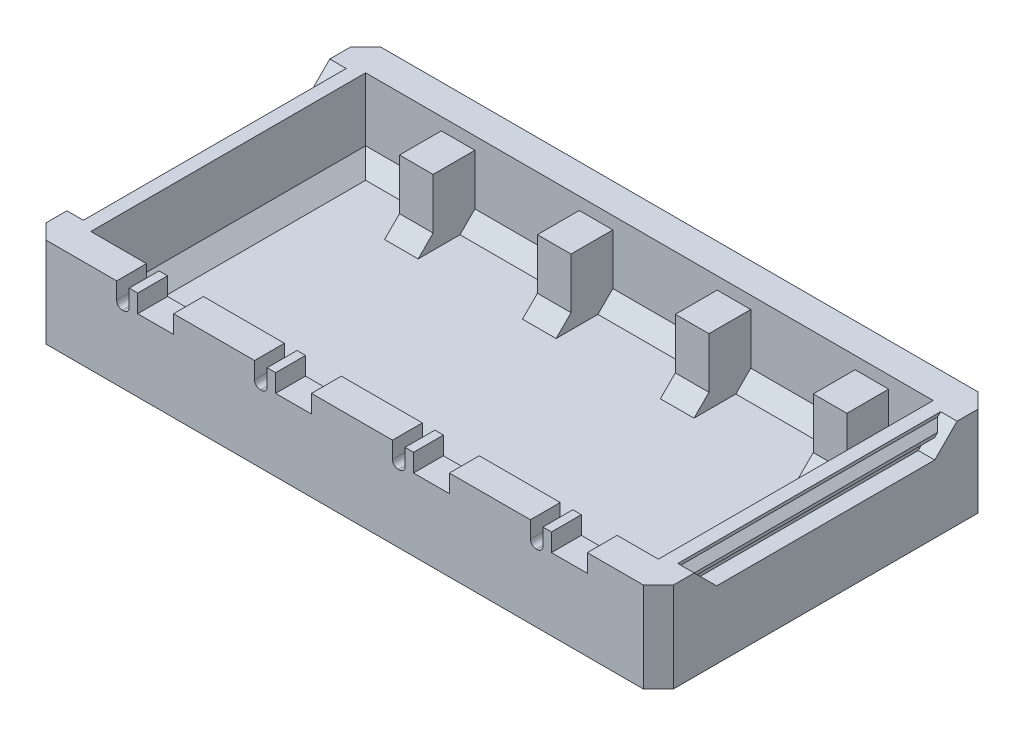
SolidWorks part; units mm, degrees
ref_plane "Front Plane" through (0, 0, 0) normal (0, 0, 1) x (1, 0, 0)
ref_plane "Top Plane" through (0, 0, 0) normal (0, 1, 0) x (1, 0, 0)
ref_plane "Right Plane" through (0, 0, 0) normal (1, 0, 0) x (0, 0, -1)
sketch "Sketch1" plane through (0, 0, 0) normal (0, 1, 0) x (1, 0, 0)
  line L0 (-98.0961, -62.3378) -> (-93.9186, -62.3378)
  line L1 (-36.993, -62.3378) -> (-32.8155, -62.3378)
  line L3 (-91.424, 17.3176) -> (-116.5294, 17.3176)
  line L4 (-120.5294, 26.5283) -> (130.2431, 26.5283)
  line L5 (130.2431, 26.5283) -> (144.4706, 12.3007)
  line L6 (144.4706, 12.3007) -> (144.4706, -73.4717)
  line L7 (-120.5294, -73.4717) -> (-120.5294, 26.5283)
  line L8 (-120.5294, -73.4717) -> (144.4706, -73.4717)
  line L9 (-13.46, -3.1584) -> (-13.46, 8.5813)
  line L10 (-13.46, 8.5813) -> (-19.078, 8.5283)
  line L11 (-19.078, 8.5283) -> (-19.078, 17.3176)
  line L12 (-19.078, 17.3176) -> (-30.321, 17.3176)
  line L13 (-30.321, 17.3176) -> (-30.321, 8.5283)
  line L14 (-30.321, 8.5283) -> (-49.7, 8.5283)
  line L15 (-49.7, 8.5283) -> (-49.7, -62.3378)
  line L16 (-49.7, -62.3378) -> (-36.993, -62.3378)
  line L17 (-36.993, -62.3378) -> (-36.993, -66.4407)
  line L18 (-36.993, -66.4407) -> (-35.5069, -66.4407)
  line L19 (-35.5069, -66.4407) -> (-35.5069, -73.7817)
  line L20 (-35.5069, -73.7817) -> (-34.1569, -73.7817)
  line L21 (-34.1569, -73.7817) -> (-34.1569, -66.2817)
  line L22 (-34.1569, -66.2817) -> (-32.8155, -66.2817)
  line L23 (-32.8155, -66.2817) -> (-32.8155, -61.9717)
  line L24 (-32.8155, -61.9717) -> (-29.96, -61.9717)
  line L25 (-29.96, -61.9717) -> (-29.96, -96.1308)
  line L26 (-29.96, -96.1308) -> (-17.96, -96.1308)
  line L27 (-17.96, -96.1308) -> (-17.96, -61.9717)
  line L28 (-17.96, -61.9717) -> (-13.46, -61.9717)
  line L29 (-13.46, -61.9717) -> (-13.46, -56.6683)
  line L30 (-13.46, -56.6683) -> (-13.46, -3.1584)
  line L31 (50.8938, -3.1584) -> (50.8938, 8.5813)
  line L32 (50.8938, 8.5813) -> (45.2757, 8.5283)
  line L33 (45.2757, 8.5283) -> (45.2757, 17.3176)
  line L34 (45.2757, 17.3176) -> (34.0298, 17.3176)
  line L35 (34.0298, 17.3176) -> (34.0298, 8.5283)
  line L36 (34.0298, 8.5283) -> (14.65, 8.5283)
  line L37 (14.65, 8.5283) -> (14.65, -62.3378)
  line L38 (14.65, -62.3378) -> (27.3577, -62.3378)
  line L39 (27.3577, -62.3378) -> (27.3577, -66.4407)
  line L40 (27.3577, -66.4407) -> (28.8438, -66.4407)
  line L41 (28.8438, -66.4407) -> (28.8438, -73.7817)
  line L42 (28.8438, -73.7817) -> (30.1938, -73.7817)
  line L43 (30.1938, -73.7817) -> (30.1938, -66.2817)
  line L44 (30.1938, -66.2817) -> (31.5352, -66.2817)
  line L45 (31.5352, -66.2817) -> (31.5352, -61.9717)
  line L46 (31.5352, -61.9717) -> (34.3938, -61.9717)
  line L47 (34.3938, -61.9717) -> (34.3938, -96.1308)
  line L48 (34.3938, -96.1308) -> (46.3938, -96.1308)
  line L49 (46.3938, -96.1308) -> (46.3938, -61.9717)
  line L50 (46.3938, -61.9717) -> (50.8938, -61.9717)
  line L51 (50.8938, -61.9717) -> (50.8938, -56.6683)
  line L52 (50.8938, -56.6683) -> (50.8938, -3.1584)
  line L53 (118.1875, -3.1584) -> (118.1875, 8.5813)
  line L54 (118.1875, 8.5813) -> (112.5695, 8.5283)
  line L55 (112.5695, 8.5283) -> (112.5695, 17.3176)
  line L56 (112.5695, 17.3176) -> (101.3235, 17.3176)
  line L57 (101.3235, 17.3176) -> (101.3235, 8.5283)
  line L58 (101.3235, 8.5283) -> (81.9438, 8.5283)
  line L59 (81.9438, 8.5283) -> (81.9438, -62.3378)
  line L60 (81.9438, -62.3378) -> (94.6515, -62.3378)
  line L61 (94.6515, -62.3378) -> (94.6515, -66.4407)
  line L62 (94.6515, -66.4407) -> (96.1375, -66.4407)
  line L63 (96.1375, -66.4407) -> (96.1375, -73.7817)
  line L64 (96.1375, -73.7817) -> (97.4875, -73.7817)
  line L65 (97.4875, -73.7817) -> (97.4875, -66.2817)
  line L66 (97.4875, -66.2817) -> (98.829, -66.2817)
  line L67 (98.829, -66.2817) -> (98.829, -61.9717)
  line L68 (98.829, -61.9717) -> (101.6875, -61.9717)
  line L69 (101.6875, -61.9717) -> (101.6875, -96.1308)
  line L70 (101.6875, -96.1308) -> (113.6875, -96.1308)
  line L71 (113.6875, -96.1308) -> (113.6875, -61.9717)
  line L72 (113.6875, -61.9717) -> (118.1875, -61.9717)
  line L73 (118.1875, -61.9717) -> (118.1875, -56.6683)
  line L74 (118.1875, -56.6683) -> (118.1875, -3.1584)
  line L77 (-80.178, 17.3176) -> (-91.424, 17.3176)
  line L79 (-116.5294, 22.5283) -> (-116.5294, -69.4717)
  line L80 (-116.5294, -69.4717) -> (140.4706, -69.4717)
  line L81 (128.5862, 22.5283) -> (140.4706, 10.6439)
  line L83 (140.4706, -69.4717) -> (140.4706, 10.6439)
  line L84 (-116.5294, 22.5283) -> (128.5862, 22.5283)
  line L86 (-110.8038, -62.3378) -> (-98.0961, -62.3378)
  line L87 (-98.0961, -62.3378) -> (-98.0961, -66.4407)
  line L88 (-98.0961, -66.4407) -> (-96.61, -66.4407)
  line L89 (-96.61, -66.4407) -> (-96.61, -73.7817)
  line L90 (-96.61, -73.7817) -> (-95.26, -73.7817)
  line L91 (-95.26, -73.7817) -> (-95.26, -66.2817)
  line L92 (-95.26, -66.2817) -> (-93.9186, -66.2817)
  line L93 (-93.9186, -66.2817) -> (-93.9186, -61.9717)
  line L94 (-93.9186, -61.9717) -> (-91.06, -61.9717)
  line L95 (-91.06, -61.9717) -> (-91.06, -96.1308)
  line L96 (-91.06, -96.1308) -> (-79.06, -96.1308)
  line L97 (-79.06, -96.1308) -> (-79.06, -61.9717)
  line L98 (-79.06, -61.9717) -> (-74.56, -61.9717)
  line L99 (-74.56, -61.9717) -> (-74.56, -56.6683)
  line L101 (-116.5294, 17.3176) -> (-116.5294, 8.5283)
  line L102 (-116.5294, 8.5283) -> (140.4706, 8.5283)
  line L103 (140.4706, 8.5283) -> (140.4706, 10.6439)
  line L104 (133.7969, 17.3176) -> (-91.424, 17.3176)
  line L105 (27.3577, -62.3378) -> (31.5352, -62.3378)
  line L106 (94.6515, -62.3378) -> (98.829, -62.3378)
  line L107 (-91.424, 17.3176) -> (-91.424, 22.5283)
  line L108 (-91.424, 22.5283) -> (-80.178, 22.5283)
  line L109 (-80.178, 22.5283) -> (-80.178, 17.3176)
  line L110 (-30.321, 17.3176) -> (-30.321, 22.5283)
  line L111 (-30.321, 22.5283) -> (-19.078, 22.5283)
  line L112 (-19.078, 22.5283) -> (-19.078, 17.3176)
  line L113 (34.0298, 17.3176) -> (34.0298, 22.5283)
  line L114 (34.0298, 22.5283) -> (45.2757, 22.5283)
  line L115 (45.2757, 22.5283) -> (45.2757, 17.3176)
  line L116 (101.3235, 17.3176) -> (101.3235, 22.5283)
  line L117 (101.3235, 22.5283) -> (112.5695, 22.5283)
  line L118 (112.5695, 22.5283) -> (112.5695, 17.3176)
sketch "Sketch2" plane through (0, 0, 0) normal (0, 1, 0) x (1, 0, 0)
  line L3 (-116.5294, 22.5283) -> (128.5862, 22.5283) construction
  line L4 (79.4706, 22.5283) -> (79.4706, -69.4717)
  line L5 (-116.5294, -69.4717) -> (140.4706, -69.4717) construction
  line L8 (-110.5294, 22.5283) -> (79.4706, 22.5283)
  line L10 (-110.5294, 22.5283) -> (-110.5294, -69.4717)
  line L12 (-110.5294, -69.4717) -> (79.4706, -69.4717)
  line L19 (89.4706, -79.4717) -> (-120.5294, -79.4717)
  line L20 (-120.5294, -79.4717) -> (-120.5294, 32.5283)
  line L21 (-120.5294, 32.5283) -> (89.4706, 32.5283)
  line L22 (89.4706, -79.4717) -> (89.4706, 32.5283)
  dimension "D1" = 10
extrude "Boss-Extrude1" add sketch "Sketch2" along normal blind 30.16
sketch "Sketch3" plane through (0, 0, 0) normal (0, -1, 0) x (1, 0, 0)
  line L1 (-120.5294, 79.4717) -> (89.4706, 79.4717)
  line L2 (-120.5294, 79.4717) -> (-120.5294, -32.5283)
  line L3 (-120.5294, -32.5283) -> (89.4706, -32.5283)
  line L4 (89.4706, 79.4717) -> (89.4706, -32.5283)
extrude "Boss-Extrude2" add sketch "Sketch3" against normal blind 4 separate body
sketch "Sketch4" plane through (0, 4, 0) normal (0, 1, 0) x (1, 0, 0)
  line L0 (-73.9394, 22.5283) -> (-73.9394, 8.5283)
  line L1 (-116.5294, 22.5283) -> (128.5862, 22.5283) construction
  line L2 (-116.5294, 8.5283) -> (140.4706, 8.5283) construction
  line L3 (-73.9394, 8.5283) -> (-85.1894, 8.5283)
  line L4 (-85.1894, 8.5283) -> (-85.1894, 22.5283)
  line L5 (-85.1894, 22.5283) -> (-73.9394, 22.5283)
  line L6 (-110.5294, 22.5283) -> (-110.5294, -69.4717) construction
  line L7 (-27.7694, 22.5283) -> (-27.7694, 8.5283)
  line L8 (-27.7694, 8.5283) -> (-39.0194, 8.5283)
  line L9 (-39.0194, 8.5283) -> (-39.0194, 22.5283)
  line L10 (-39.0194, 22.5283) -> (-27.7694, 22.5283)
  line L11 (18.4006, 22.5283) -> (18.4006, 8.5283)
  line L12 (18.4006, 8.5283) -> (7.1506, 8.5283)
  line L13 (7.1506, 8.5283) -> (7.1506, 22.5283)
  line L14 (7.1506, 22.5283) -> (18.4006, 22.5283)
  line L15 (64.5706, 22.5283) -> (64.5706, 8.5283)
  line L16 (64.5706, 8.5283) -> (53.3206, 8.5283)
  line L17 (53.3206, 8.5283) -> (53.3206, 22.5283)
  line L18 (53.3206, 22.5283) -> (64.5706, 22.5283)
  dimension "D1" = 36.59
  dimension "D2" = 11.25
  dimension "D3" = 11.25
  dimension "D4" = 46.17
  dimension "D5" = 11.25
  dimension "D6" = 46.17
  dimension "D7" = 11.25
  dimension "D8" = 46.17
extrude "Boss-Extrude3" add sketch "Sketch4" along normal blind 22
sketch "Sketch5" plane through (0, 30.16, 0) normal (0, 1, 0) x (1, 0, 0)
  line L0 (-84.8294, -69.4717) -> (-84.8294, -79.4717)
  line L1 (-116.5294, -69.4717) -> (140.4706, -69.4717) construction
  line L2 (-120.5294, -79.4717) -> (89.4706, -79.4717) construction
  line L3 (-85.1894, 22.5283) -> (-85.1894, 8.5283) construction
  line L4 (-72.8294, -69.4717) -> (-72.8294, -79.4717)
  line L5 (-84.8294, -69.4717) -> (-72.8294, -69.4717)
  line L6 (-72.8294, -79.4717) -> (-84.8294, -79.4717)
  line L7 (-38.6594, -69.4717) -> (-38.6594, -79.4717)
  line L8 (-26.6594, -69.4717) -> (-26.6594, -79.4717)
  line L9 (-38.6594, -69.4717) -> (-26.6594, -69.4717)
  line L10 (-26.6594, -79.4717) -> (-38.6594, -79.4717)
  line L11 (7.5106, -69.4717) -> (7.5106, -79.4717)
  line L12 (19.5106, -69.4717) -> (19.5106, -79.4717)
  line L13 (7.5106, -69.4717) -> (19.5106, -69.4717)
  line L14 (19.5106, -79.4717) -> (7.5106, -79.4717)
  line L15 (53.6806, -69.4717) -> (53.6806, -79.4717)
  line L16 (65.6806, -69.4717) -> (65.6806, -79.4717)
  line L17 (53.6806, -69.4717) -> (65.6806, -69.4717)
  line L18 (65.6806, -79.4717) -> (53.6806, -79.4717)
  dimension "D1" = 0.36
  dimension "D2" = 12
  dimension "D3" = 12
  dimension "D4" = 12
  dimension "D5" = 12
  dimension "D6" = 46.17
  dimension "D7" = 46.17
  dimension "D8" = 46.17
extrude "Cut-Extrude1" cut sketch "Sketch5" against normal blind 6
chamfer "Chamfer2" distance 5 angle 45 8 edges at (35.8606, 4, -22.5283) (-10.3094, 4, -22.5283) (-56.4794, 4, -22.5283) (72.0206, 4, -22.5283) (79.4706, 4, 23.4717) (-15.5294, 4, 69.4717) (-97.8594, 4, -22.5283) (-110.5294, 4, 23.4717)
sketch "Sketch6" plane through (-120.5294, 0, 0) normal (-1, 0, 0) x (0, 0, 1)
  line L0 (-20.5283, 30.16) -> (67.4717, 30.16)
  line L1 (-32.5283, 30.16) -> (79.4717, 30.16) construction
  line L4 (67.4717, 30.16) -> (59.9717, 22.66)
  line L5 (-20.5283, 30.16) -> (-13.0283, 22.66)
  line L6 (-13.0283, 22.66) -> (59.9717, 22.66)
  point P10 (23.4717, 22.66)
extrude "Cut-Extrude2" cut sketch "Sketch6" against normal blind 5.5
sketch "Sketch8" plane through (89.4706, 0, 0) normal (1, 0, 0) x (0, 0, -1)
  line L0 (20.5283, 30.16) -> (13.0283, 22.66)
  line L1 (-79.4717, 30.16) -> (32.5283, 30.16) construction
  line L3 (-67.4717, 30.16) -> (20.5283, 30.16)
  line L5 (-67.4717, 30.16) -> (-59.9717, 22.66)
  line L6 (-59.9717, 22.66) -> (13.0283, 22.66)
  point P5 (-23.4717, 22.66)
extrude "Cut-Extrude3" cut sketch "Sketch8" against normal blind 5.5
sketch "Sketch9" plane through (0, 30.16, 0) normal (0, 1, 0) x (1, 0, 0)
  line L0 (-87.6894, -69.4717) -> (-87.6894, -79.4717)
  line L1 (79.4706, -69.4717) -> (-110.5294, -69.4717) construction
  line L2 (-120.5294, -79.4717) -> (-84.8294, -79.4717) construction
  line L3 (-91.8894, -69.4717) -> (-91.8894, -79.4717)
  line L5 (-84.8294, -69.4717) -> (-84.8294, -79.4717) construction
  line L6 (-91.8894, -69.4717) -> (-87.6894, -69.4717)
  line L7 (-91.8894, -79.4717) -> (-87.6894, -79.4717)
  line L8 (50.8206, -69.4717) -> (50.8206, -79.4717)
  line L9 (46.6206, -69.4717) -> (46.6206, -79.4717)
  line L10 (46.6206, -69.4717) -> (50.8206, -69.4717)
  line L11 (46.6206, -79.4717) -> (50.8206, -79.4717)
  line L12 (4.6506, -69.4717) -> (4.6506, -79.4717)
  line L13 (0.4506, -69.4717) -> (0.4506, -79.4717)
  line L14 (0.4506, -69.4717) -> (4.6506, -69.4717)
  line L15 (0.4506, -79.4717) -> (4.6506, -79.4717)
  line L16 (-41.5194, -69.4717) -> (-41.5194, -79.4717)
  line L17 (-45.7194, -69.4717) -> (-45.7194, -79.4717)
  line L18 (-45.7194, -69.4717) -> (-41.5194, -69.4717)
  line L19 (-45.7194, -79.4717) -> (-41.5194, -79.4717)
  line L20 (-38.6594, -69.4717) -> (-38.6594, -79.4717) construction
  line L21 (7.5106, -69.4717) -> (7.5106, -79.4717) construction
  line L22 (53.6806, -69.4717) -> (53.6806, -79.4717) construction
  dimension "D1" = 2.86
  dimension "D2" = 4.2
  dimension "D3" = 2.86
  dimension "D4" = 2.86
  dimension "D5" = 2.86
extrude "Cut-Extrude4" cut sketch "Sketch9" against normal blind 7.5
fillet "Fillet1" radius 1.88 8 edges at (-45.7194, 22.66, 74.4717) (0.4506, 22.66, 74.4717) (46.6206, 22.66, 74.4717) (-41.5194, 22.66, 74.4717) (4.6506, 22.66, 74.4717) (50.8206, 22.66, 74.4717) (-87.6894, 22.66, 74.4717) (-91.8894, 22.66, 74.4717)
chamfer "Chamfer3" distance 5 angle 45 4 edges at (58.9456, 4, -8.5283) (12.7756, 4, -8.5283) (-33.3944, 4, -8.5283) (-79.5644, 4, -8.5283)
chamfer "Chamfer4" distance 5 angle 45 4 edges at (-120.5294, 15.08, -32.5283) (89.4706, 15.08, -32.5283) (89.4706, 15.08, 79.4717) (-120.5294, 15.08, 79.4717)
sketch "Sketch10" plane through (0, 0, 79.4717) normal (0, 0, 1) x (1, 0, 0)
  line L0 (83.9706, 29.16) -> (86.2206, 26.91)
  line L2 (86.2206, 25.91) -> (83.9706, 23.66)
  line L3 (86.2206, 26.91) -> (86.2206, 25.91)
  line L6 (83.9706, 29.16) -> (83.9706, 23.66)
  line L10 (-115.0294, 29.16) -> (-115.0294, 23.66)
  line L11 (-117.2794, 26.91) -> (-117.2794, 25.91)
  line L12 (-117.2794, 25.91) -> (-115.0294, 23.66)
  line L13 (-115.0294, 29.16) -> (-117.2794, 26.91)
extrude "Boss-Extrude4" add sketch "Sketch10" against normal blind 90 from offset 10
